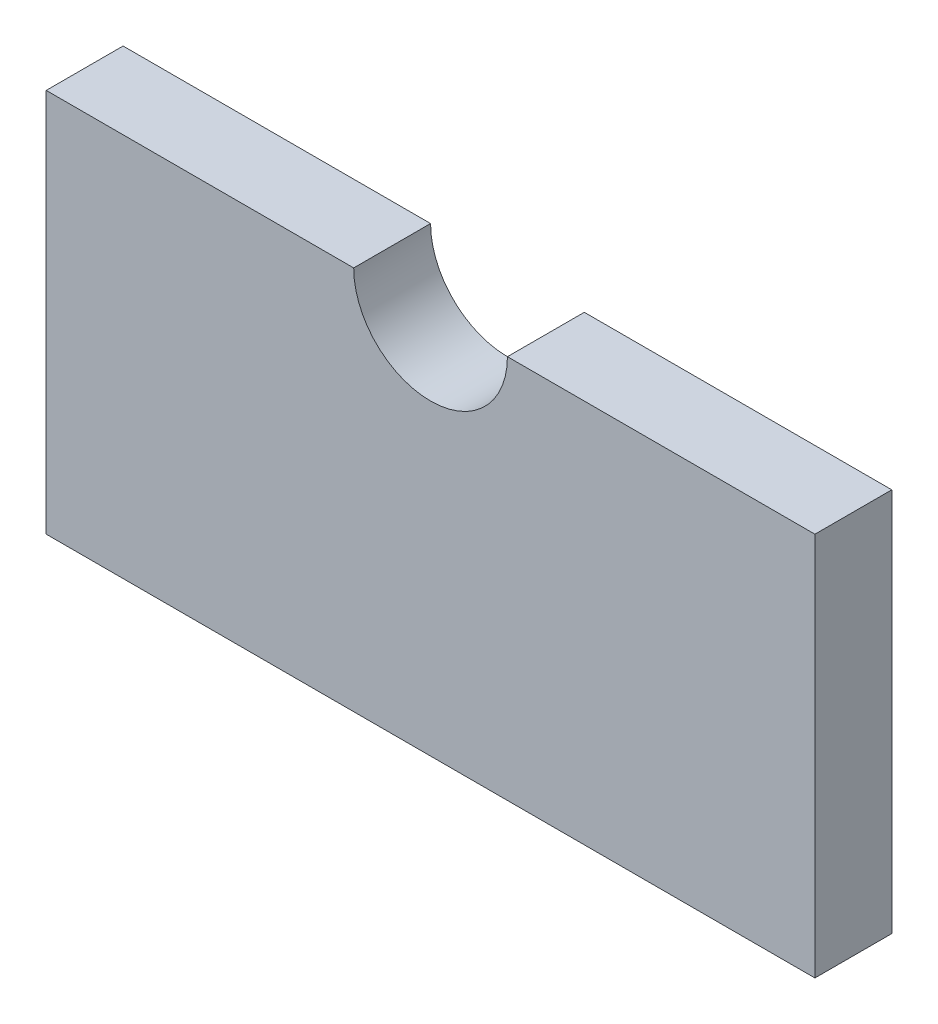
SolidWorks part; units mm, degrees
ref_plane "Front Plane" through (0, 0, 0) normal (0, 0, 1) x (1, 0, 0)
ref_plane "Top Plane" through (0, 0, 0) normal (0, 1, 0) x (1, 0, 0)
ref_plane "Right Plane" through (0, 0, 0) normal (1, 0, 0) x (0, 0, -1)
sketch "Sketch2" plane through (0, 0, 0) normal (0, 0, 1) x (1, 0, 0)
  line L1 (-25, 12.5) -> (25, 12.5)
  line L2 (-25, 12.5) -> (-25, -12.5)
  line L3 (-25, -12.5) -> (25, -12.5)
  line L4 (25, 12.5) -> (25, -12.5)
  line L5 (-25, 12.5) -> (25, -12.5) construction
  line L6 (-25, -12.5) -> (25, 12.5) construction
  point P0 (0, 0)
  dimension "D1" = 50
  dimension "D2" = 25
extrude "Boss-Extrude2" add sketch "Sketch2" along normal blind 5 contours L2 L1 L4 L3
sketch "Sketch6" plane through (0, 0, 0) normal (0, 0, 1) x (1, 0, 0)
  line L0 (-25, 12.5) -> (25, 12.5) construction
  line L1 (-5, 12.5) -> (5, 12.5)
  arc A0 (5, 12.5) -> (-5, 12.5) centre (0, 12.5) cw
  dimension "D1" = 5
extrude "Cut-Extrude1" cut sketch "Sketch6" along normal blind 5
